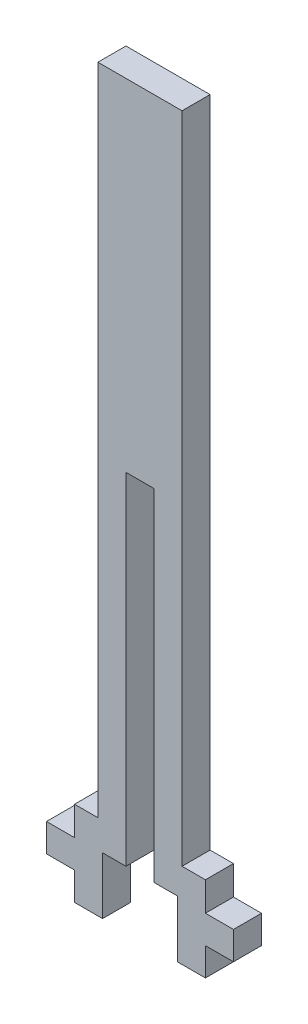
SolidWorks part; units mm, degrees
material "Plain Carbon Steel"
ref_plane "Front Plane" through (0, 0, 0) normal (0, 0, 1) x (1, 0, 0)
ref_plane "Top Plane" through (0, 0, 0) normal (0, 1, 0) x (1, 0, 0)
ref_plane "Right Plane" through (0, 0, 0) normal (1, 0, 0) x (0, 0, -1)
sketch "스케치1" plane through (0, 0, 0) normal (0, 0, 1) x (1, 0, 0)
  line L0 (0, 0) -> (0, -33.444) construction
  line L1 (-7, -39.544) -> (7, -39.544) construction
  line L2 (-7, -39.544) -> (-7, 39.544) construction
  line L3 (-7, 39.544) -> (7, 39.544) construction
  line L4 (7, -39.544) -> (7, 39.544) construction
  line L5 (-7, -39.544) -> (7, 39.544) construction
  line L6 (-7, 39.544) -> (7, -39.544) construction
  line L7 (-4, -39.544) -> (4, -39.544) construction
  line L8 (-4, -39.544) -> (-4, -33.444)
  line L9 (-4, -33.444) -> (4, -33.444)
  line L10 (4, -39.544) -> (4, -33.444)
  line L11 (-4, -39.544) -> (4, -33.444) construction
  line L12 (-4, -33.444) -> (4, -39.544) construction
  line L13 (4.5, -30.444) -> (-4.5, -30.444) construction
  line L14 (7, -30.444) -> (4.5, -30.444)
  line L15 (7, -30.444) -> (7, 39.544) construction
  line L16 (7, 39.544) -> (4.5, 39.544) construction
  line L17 (4.5, -30.444) -> (4.5, 39.544) construction
  line L18 (7, -30.444) -> (4.5, 39.544) construction
  line L19 (7, 39.544) -> (4.5, -30.444) construction
  line L20 (-4.5, 39.544) -> (-7, 39.544) construction
  line L21 (-4.5, 39.544) -> (-4.5, -30.444) construction
  line L22 (-4.5, -30.444) -> (-7, -30.444)
  line L23 (-7, 39.544) -> (-7, -30.444) construction
  line L24 (-4.5, 39.544) -> (-7, -30.444) construction
  line L25 (-4.5, -30.444) -> (-7, 39.544) construction
  line L26 (4, -39.544) -> (7, -39.544)
  line L27 (-1.5, 30.444) -> (1.5, 30.444) construction
  line L28 (-1.5, 30.444) -> (-1.5, -30.444) construction
  line L29 (-1.5, -30.444) -> (1.5, -30.444) construction
  line L30 (1.5, 30.444) -> (1.5, -30.444) construction
  line L31 (-1.5, 30.444) -> (1.5, -30.444) construction
  line L32 (-1.5, -30.444) -> (1.5, 30.444) construction
  line L33 (7, -39.544) -> (7, -30.444)
  line L34 (-7, -30.444) -> (-7, -39.544)
  line L35 (-7, -39.544) -> (-4, -39.544)
  line L36 (-4.5, 39.544) -> (-7, 39.544) construction
  line L37 (-7, 39.544) -> (-7, -39.544)
  line L38 (4.5, 39.544) -> (7, 39.544) construction
  line L39 (-4.5, -30.444) -> (-4.5, 39.544)
  line L40 (4.5, 39.544) -> (4.5, -30.444)
  line L41 (-4.5, 39.544) -> (4.5, 39.544)
  point P0 (0, 0)
  point P10 (0, -36.494)
  point P16 (5.75, 4.55)
  point P20 (-5.75, 4.55)
  dimension "D1" = 69.988
  dimension "D2" = 3
  dimension "D3" = 8
  dimension "D4" = 6.1
  dimension "D5" = 3
  dimension "D6" = 3
  dimension "D7" = 3
extrude "보스-돌출1" add sketch "스케치1" along normal blind 3 contours L41 L39 L22 L34 L35 L8 L9 L10 L26 L33 L14 L40
sketch "스케치2" plane through (0, 0, 0) normal (0, 0, -1) x (-1, 0, 0)
  line L0 (0, 39.544) -> (0, -33.444) construction
  line L1 (4.5, 39.544) -> (-4.5, 39.544) construction
  line L2 (4, -33.444) -> (-4, -33.444) construction
  line L4 (-1.5, -33.444) -> (1.5, -33.444)
  line L5 (-1.5, -33.444) -> (-1.5, 3.05)
  line L6 (-1.5, 3.05) -> (1.5, 3.05)
  line L7 (1.5, -33.444) -> (1.5, 3.05)
  line L8 (-1.5, -33.444) -> (1.5, 3.05) construction
  line L9 (-1.5, 3.05) -> (1.5, -33.444) construction
  point P6 (0, -15.197)
  point P11 (0, 3.05)
  dimension "D1" = 3
extrude "컷-돌출1" cut sketch "스케치2" against normal up to surface (3 mm away) up to face at (0, -22.3127, 3)
sketch "스케치3" plane through (0, 0, 3) normal (0, 0, 1) x (1, 0, 0)
  line L0 (-7, -30.444) -> (-7, -39.544) construction
  line L1 (-7, -33.544) -> (-10, -33.544)
  line L2 (-7, -33.544) -> (-7, -36.544)
  line L3 (-7, -36.544) -> (-10, -36.544)
  line L4 (-10, -33.544) -> (-10, -36.544)
  line L5 (-7, -33.544) -> (-10, -36.544) construction
  line L6 (-7, -36.544) -> (-10, -33.544) construction
  line L7 (7, -39.544) -> (7, -30.444) construction
  line L8 (7, -33.544) -> (10, -33.544)
  line L9 (7, -33.544) -> (7, -36.544)
  line L10 (7, -36.544) -> (10, -36.544)
  line L11 (10, -33.544) -> (10, -36.544)
  line L12 (7, -33.544) -> (10, -36.544) construction
  line L13 (7, -36.544) -> (10, -33.544) construction
  line L14 (-7, -39.544) -> (-4, -39.544) construction
  line L15 (4, -39.544) -> (7, -39.544) construction
  point P4 (-8.5, -35.044)
  point P11 (8.5, -35.044)
  dimension "D1" = 3
  dimension "D2" = 3
  dimension "D3" = 3
  dimension "D4" = 3
  dimension "D5" = 3
  dimension "D6" = 3
extrude "보스-돌출2" add sketch "스케치3" against normal blind 3
